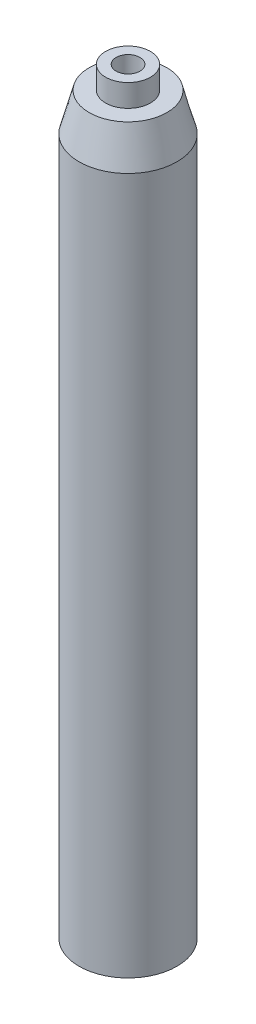
SolidWorks part; units mm, degrees
ref_plane "前视基准面" through (0, 0, 0) normal (0, 0, 1) x (1, 0, 0)
ref_plane "上视基准面" through (0, 0, 0) normal (0, 1, 0) x (1, 0, 0)
ref_plane "右视基准面" through (0, 0, 0) normal (1, 0, 0) x (0, 0, -1)
sketch "草图1" plane through (0, 0, 0) normal (0, 0, 1) x (1, 0, 0)
  line L0 (1.3526, 70.7746) -> (0, 69.9619)
  line L1 (0, 69.9619) -> (0, 15.9003)
  line L2 (0, 15.9003) -> (1.3526, 15.0876)
  line L3 (1.3526, 15.0876) -> (1.3526, 0)
  line L4 (1.3526, 0) -> (5.5563, 0)
  line L5 (5.5563, 0) -> (5.5563, 79.0463)
  line L6 (5.5563, 79.0463) -> (4.4132, 83.312)
  line L7 (4.4132, 83.312) -> (2.54, 83.312)
  line L8 (2.54, 83.312) -> (2.54, 85.852)
  line L9 (2.54, 85.852) -> (1.3526, 85.852)
  line L10 (1.3526, 85.852) -> (1.3526, 70.7746)
  line L11 (0, 85.852) -> (0, 0) construction
revolve "旋转1" add sketch "草图1" angle 360 about L11
